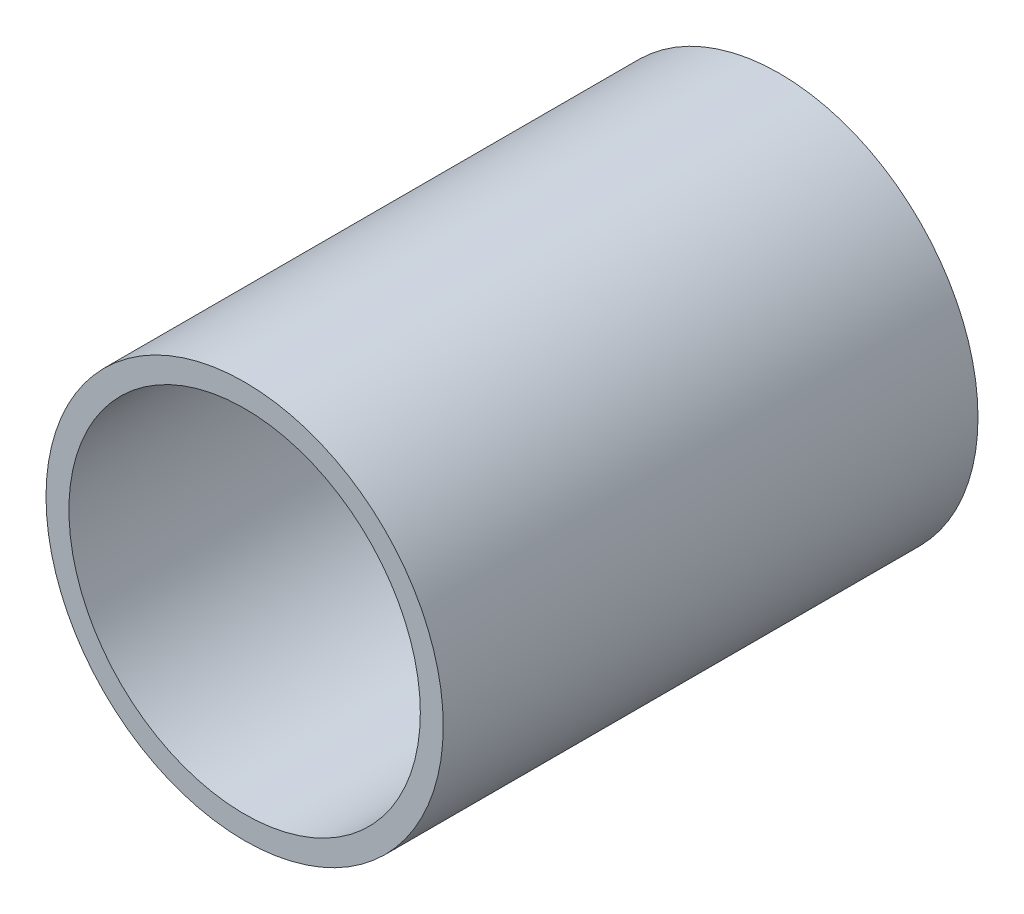
SolidWorks part; units mm, degrees
ref_plane "Front Plane" through (0, 0, 0) normal (0, 0, 1) x (1, 0, 0)
ref_plane "Top Plane" through (0, 0, 0) normal (0, 1, 0) x (1, 0, 0)
ref_plane "Right Plane" through (0, 0, 0) normal (1, 0, 0) x (0, 0, -1)
sketch "Sketch1" plane through (0, 0, 0) normal (0, 0, 1) x (1, 0, 0)
  circle A0 centre (0, 0) radius 26
  circle A1 centre (0, 0) radius 23
  dimension "D1" = 52
  dimension "D2" = 46
extrude "Boss-Extrude1" add sketch "Sketch1" along normal blind 70
